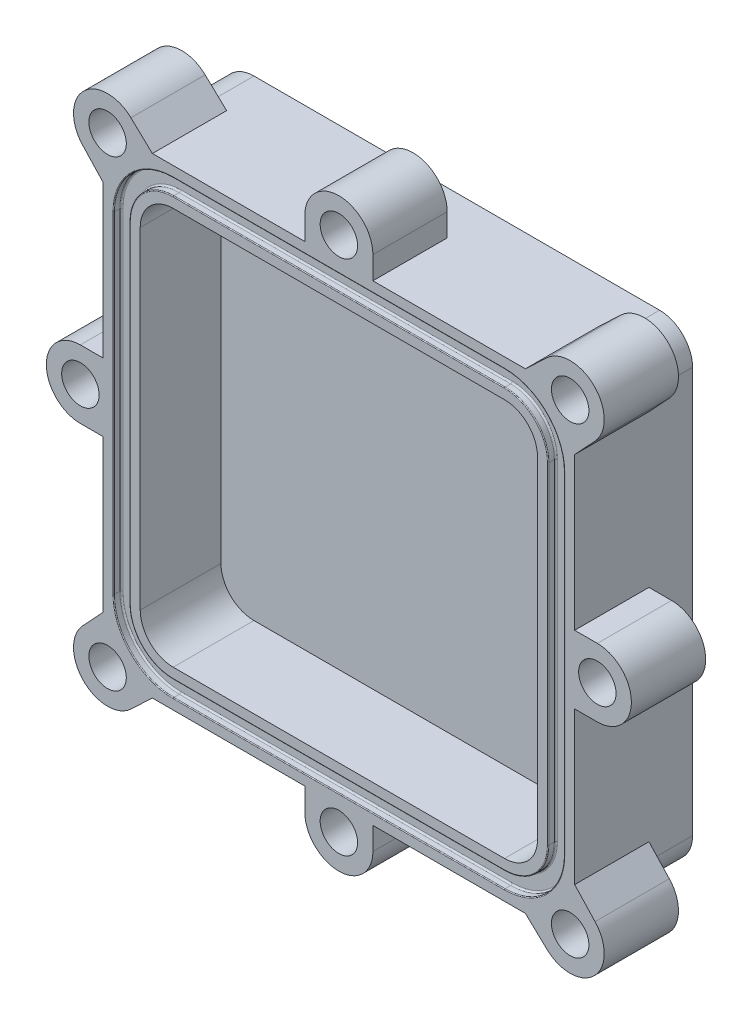
SolidWorks part; units mm, degrees
material "Custom Plastic"
ref_plane "X-Y Datum" through (0, 0, 0) normal (0, 0, 1) x (1, 0, 0)
ref_plane "X-Z Datum" through (0, 0, 0) normal (0, 1, 0) x (1, 0, 0)
ref_plane "Y-Z Datum" through (0, 0, 0) normal (1, 0, 0) x (0, 0, -1)
sketch "Sketch1" plane through (0, 0, 0) normal (0, 0, 1) x (1, 0, 0)
  line L1 (-38.1, 38.1) -> (38.1, 38.1)
  line L2 (-38.1, 38.1) -> (-38.1, -38.1)
  line L3 (-38.1, -38.1) -> (38.1, -38.1)
  line L4 (38.1, 38.1) -> (38.1, -38.1)
  line L5 (-38.1, 38.1) -> (38.1, -38.1) construction
  line L6 (-38.1, -38.1) -> (38.1, 38.1) construction
  point P0 (0, 0)
  dimension "D1" = 76.2
  dimension "D2" = 76.2
extrude "Boss-Extrude1" add sketch "Sketch1" along normal blind 19.05
shell "Shell4" thickness 6
fillet "Fillet3" radius 5.334 4 edges at (-32.1, 32.1, 12.525) (32.1, 32.1, 12.525) (32.1, -32.1, 12.525) (-32.1, -32.1, 12.525)
fillet "Fillet4" radius 5.334 4 edges at (-38.1, 38.1, 9.525) (-38.1, -38.1, 9.525) (38.1, -38.1, 9.525) (38.1, 38.1, 9.525)
sketch "Sketch3" plane through (0, 0, 19.05) normal (0, 0, 1) x (1, 0, 0)
  line L24 (36.3827, -26.766) -> (36.3827, 26.766)
  line L25 (26.766, 36.3827) -> (-26.766, 36.3827)
  line L26 (-36.3827, 26.766) -> (-36.3827, -26.766)
  line L27 (-26.766, -36.3827) -> (26.766, -36.3827)
  line L28 (35.1, -26.766) -> (35.1, 26.766)
  line L29 (-26.766, -35.1) -> (26.766, -35.1)
  line L30 (-35.1, 26.766) -> (-35.1, -26.766)
  line L31 (26.766, 35.1) -> (-26.766, 35.1)
  line L32 (35.1, -26.766) -> (35.1, 26.766) construction
  line L33 (-26.766, -35.1) -> (26.766, -35.1) construction
  line L34 (-35.1, 26.766) -> (-35.1, -26.766) construction
  line L35 (26.766, 35.1) -> (-26.766, 35.1) construction
  line L36 (-33.8173, 26.766) -> (-33.8173, -26.766)
  line L37 (-26.766, -33.8173) -> (26.766, -33.8173)
  line L38 (33.8173, -26.766) -> (33.8173, 26.766)
  line L39 (26.766, 33.8173) -> (-26.766, 33.8173)
  arc A16 (36.3827, 26.766) -> (26.766, 36.3827) centre (26.766, 26.766) ccw
  arc A17 (-26.766, 36.3827) -> (-36.3827, 26.766) centre (-26.766, 26.766) ccw
  arc A18 (-36.3827, -26.766) -> (-26.766, -36.3827) centre (-26.766, -26.766) ccw
  arc A19 (26.766, -36.3827) -> (36.3827, -26.766) centre (26.766, -26.766) ccw
  arc A20 (35.1, 26.766) -> (26.766, 35.1) centre (26.766, 26.766) ccw
  arc A21 (26.766, -35.1) -> (35.1, -26.766) centre (26.766, -26.766) ccw
  arc A22 (-35.1, -26.766) -> (-26.766, -35.1) centre (-26.766, -26.766) ccw
  arc A23 (-26.766, 35.1) -> (-35.1, 26.766) centre (-26.766, 26.766) ccw
  arc A24 (35.1, 26.766) -> (26.766, 35.1) centre (26.766, 26.766) ccw construction
  arc A25 (26.766, -35.1) -> (35.1, -26.766) centre (26.766, -26.766) ccw construction
  arc A26 (-35.1, -26.766) -> (-26.766, -35.1) centre (-26.766, -26.766) ccw construction
  arc A27 (-26.766, 35.1) -> (-35.1, 26.766) centre (-26.766, 26.766) ccw construction
  arc A28 (-33.8173, -26.766) -> (-26.766, -33.8173) centre (-26.766, -26.766) ccw
  arc A29 (26.766, -33.8173) -> (33.8173, -26.766) centre (26.766, -26.766) ccw
  arc A30 (33.8173, 26.766) -> (26.766, 33.8173) centre (26.766, 26.766) ccw
  arc A31 (-26.766, 33.8173) -> (-33.8173, 26.766) centre (-26.766, 26.766) ccw
  dimension "D4" = 7.0513
  dimension "D5" = 2.5654
  dimension "D1" = 3
  dimension "D2" = 1.2827
  dimension "D3" = 1.2827
extrude "Cut-Extrude1" cut sketch "Sketch3" against normal blind 1.2446
fillet "Fillet5" radius 0.254 16 edges at (-31.752, 31.752, 17.8054) (0, 33.8173, 17.8054) (31.752, 31.752, 17.8054) (33.8173, 0, 17.8054) (31.752, -31.752, 17.8054) (0, -33.8173, 17.8054) (-31.752, -31.752, 17.8054) (-33.566, 33.566, 17.8054) (0, 36.3827, 17.8054) (33.566, 33.566, 17.8054) (36.3827, 0, 17.8054) (33.566, -33.566, 17.8054) (0, -36.3827, 17.8054) (-33.566, -33.566, 17.8054) (-33.8173, 0, 17.8054) (-36.3827, 0, 17.8054)
fillet "Fillet6" radius 0.127 16 edges at (-33.8173, 0, 19.05) (-31.752, 31.752, 19.05) (0, 33.8173, 19.05) (31.752, 31.752, 19.05) (33.8173, 0, 19.05) (31.752, -31.752, 19.05) (0, -33.8173, 19.05) (-33.566, 33.566, 19.05) (0, 36.3827, 19.05) (33.566, 33.566, 19.05) (36.3827, 0, 19.05) (33.566, -33.566, 19.05) (0, -36.3827, 19.05) (-33.566, -33.566, 19.05) (-31.752, -31.752, 19.05) (-36.3827, 0, 19.05)
sketch "Sketch5" plane through (0, 0, 19.05) normal (0, 0, 1) x (1, 0, 0)
  line L0 (26.766, -26.766) -> (37.3726, -37.3726) construction
  line L1 (30.1318, -38.1) -> (33.5966, -41.3716)
  line L3 (41.394, -33.6205) -> (38.1, -30.0901)
  line L5 (38.1, -32.766) -> (38.1, 32.766) construction
  line L7 (-32.766, -38.1) -> (32.766, -38.1) construction
  circle A0 centre (37.3726, -37.3726) radius 3.025
  circle A1 centre (37.3726, -37.3726) radius 3.165 construction
  circle A2 centre (37.3726, -37.3726) radius 5.5
  arc A3 (26.766, -36.5097) -> (36.5097, -26.766) centre (26.766, -26.766) ccw construction
  point P14 (33.6558, -33.6558)
  point P15 (35.1346, -35.1346)
  dimension "D1" = 6.05
  dimension "D3" = 6.33
  dimension "D4" = 11
  dimension "D5" = 2.0913
  dimension "D2" = 15
extrude "Boss-Extrude2" add sketch "Sketch5" against normal blind 12
sketch "Sketch6" plane through (0, 0, 19.05) normal (0, 0, 1) x (1, 0, 0)
  circle A0 centre (37.3726, -37.3726) radius 3.025 construction
  circle A1 centre (37.3726, -37.3726) radius 3.025
  dimension "D1" = 6.05
extrude "Cut-Extrude2" cut sketch "Sketch6" against normal blind 9
mirror "Mirror1" about plane through (0, 0, 0) normal (0, 1, 0) of "Cut-Extrude2", "Boss-Extrude2"
mirror "Mirror2" about plane through (0, 0, 0) normal (1, 0, 0) of "Mirror1", "Boss-Extrude2", "Cut-Extrude2"
sketch "Sketch7" plane through (0, 0, 19.05) normal (0, 0, 1) x (1, 0, 0)
  line L0 (0, 53.2191) -> (0, -53.2191) construction
  line L1 (-5.5, -41.7647) -> (-5.5, -38.1)
  line L2 (-30.1318, -38.1) -> (30.1318, -38.1) construction
  line L3 (5.5, -41.7647) -> (5.5, -38.1)
  line L5 (26.766, -36.5097) -> (-26.766, -36.5097) construction
  line L6 (-30.1318, -38.1) -> (30.1318, -38.1)
  circle A0 centre (0, -41.7647) radius 3.025
  circle A1 centre (0, -41.7647) radius 5.5
  circle A2 centre (0, -41.7647) radius 3.165 construction
  point P4 (0, 0)
  point P15 (0, -38.5997)
  line M7 (-30.1318, -38.1) -> (30.1318, -38.1)
  dimension "D1" = 6.05
  dimension "D2" = 11
  dimension "D3" = 6.33
  dimension "D4" = 2.09
extrude "Boss-Extrude3" add sketch "Sketch7" against normal blind 12 contours A1 L6 A0 | A0 | A1 L1 M7 | A1 L3 M7
sketch "Sketch8" plane through (0, 0, 19.05) normal (0, 0, 1) x (1, 0, 0)
  circle A0 centre (0, -41.7647) radius 3.025 construction
  circle A1 centre (0, -41.7647) radius 3.025
  dimension "D1" = 6.05
extrude "Cut-Extrude4" cut sketch "Sketch8" against normal blind 9
pattern_circular "CirPattern1" count 4 over 360 about axis through (0, 0, 0) along (0, 0, 1) of "Cut-Extrude4", "Boss-Extrude3"
